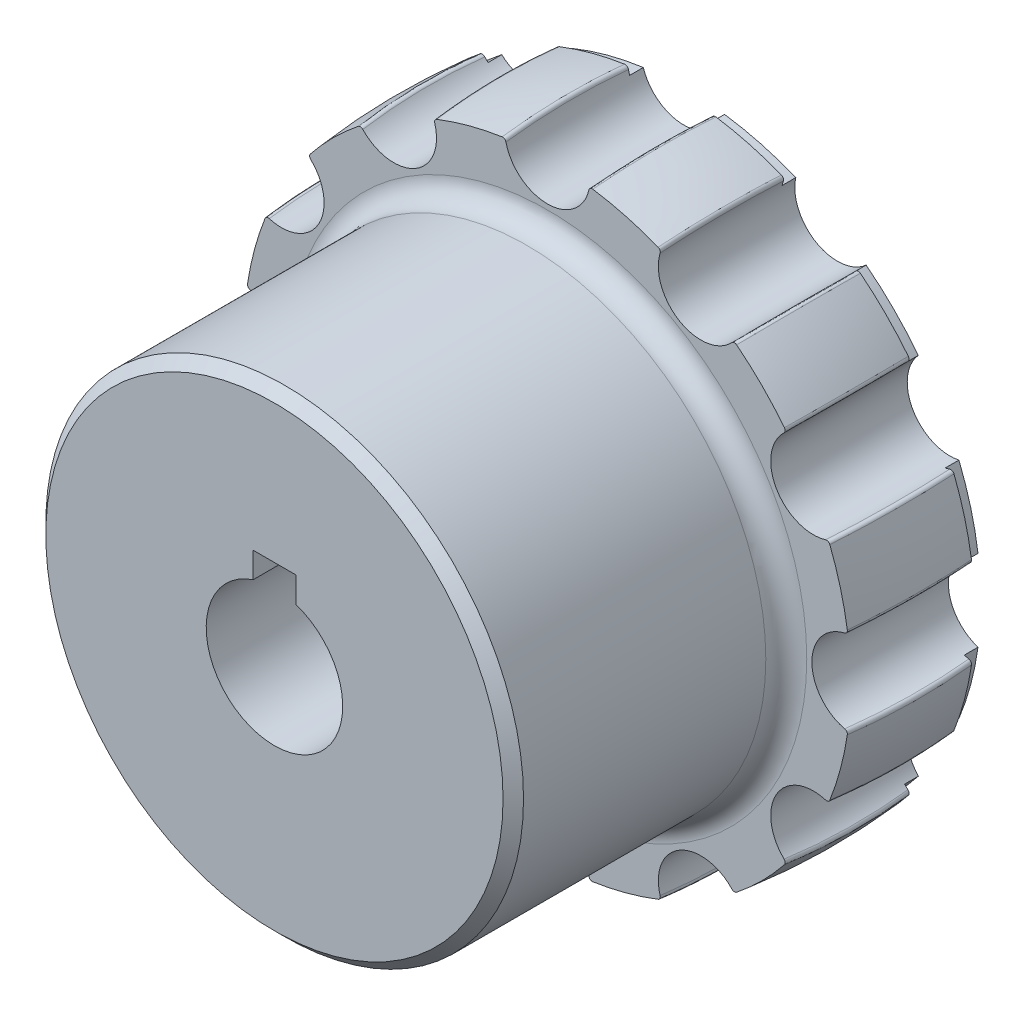
SolidWorks part; units mm, degrees
ref_plane "前视" through (0, 0, 0) normal (0, 0, 1) x (1, 0, 0)
ref_plane "上视" through (0, 0, 0) normal (0, 1, 0) x (1, 0, 0)
ref_plane "右视" through (0, 0, 0) normal (1, 0, 0) x (0, 0, -1)
sketch "草图1" plane through (0, 0, 0) normal (0, 0, 1) x (1, 0, 0)
  circle A0 centre (0, 0) radius 130
  dimension "D1" = 260
extrude "凸台-拉伸1" add sketch "草图1" along normal blind 40
sketch "草图2" plane through (0, 0, 0) normal (0, 0, 1) x (1, 0, 0)
  circle A0 centre (0, 0) radius 70
extrude "凸台-拉伸2" add sketch "草图2" along normal blind 120
sketch "草图3" plane through (0, 0, 0) normal (0, 1, 0) x (1, 0, 0)
  line L0 (0, 59.3731) -> (0, -282.5672) construction
  line L1 (130, -20) -> (-98.4903, -20) construction
  line L2 (130, -40) -> (130, 0) construction
  line L3 (-87, 0) -> (-87, -4)
  line L4 (130, 0) -> (-130, 0) construction
  line L5 (-87, -4) -> (-89.2875, -4)
  line L6 (-88.8854, -40) -> (0, -40) construction
  line L7 (-130, -40) -> (130, -40) construction
  line L8 (0, -40) -> (0, 0) construction
  line L9 (0, 0) -> (-87, 0) construction
  line L10 (-87, 0) -> (-140, 0)
  line L11 (-140, 0) -> (-140, -40)
  line L12 (-140, -40) -> (-88.8854, -40)
  line L13 (-130, 0) -> (-130, -40) construction
  line L14 (-90, -20) -> (-90, 22.025) construction
  arc A0 (-89.2875, -4) -> (-88.8854, -40) centre (90, -20) ccw
  dimension "D1" = 360
  dimension "D3" = 3
  dimension "D2" = 90
  dimension "D4" = 4
  dimension "D5" = 10
revolve "切除-旋转1" cut sketch "草图3" angle 360 about L0
sketch "草图4" plane through (0, 0, 40) normal (0, 0, 1) x (1, 0, 0)
  circle A0 centre (0, 0) radius 90 construction
  circle A1 centre (0, 90) radius 12.5
  circle A2 centre (45, 77.9423) radius 12.5
  circle A3 centre (77.9423, 45) radius 12.5
  circle A4 centre (90, 0) radius 12.5
  circle A5 centre (77.9423, -45) radius 12.5
  circle A6 centre (45, -77.9423) radius 12.5
  circle A7 centre (0, -90) radius 12.5
  circle A8 centre (-45, -77.9423) radius 12.5
  circle A9 centre (-77.9423, -45) radius 12.5
  circle A10 centre (-90, 0) radius 12.5
  circle A11 centre (-77.9423, 45) radius 12.5
  circle A12 centre (-45, 77.9423) radius 12.5
  dimension "D1" = 180
  dimension "D2" = 25
  dimension "D3" = 12
extrude "切除-拉伸1" cut sketch "草图4" against normal blind 70
fillet "圆角1" radius 6 1 edges at (70, 0, 40)
chamfer "倒角1" distance 3 angle 45 1 edges at (70, 0, 120)
fillet "圆角2" radius 1 24 edges at (-88.9043, 12.4519, 29.0559) (-89.0614, -12.4647, 14.9611) (-70.7674, 55.2358, 29.0559) (-83.3618, 33.736, 14.9611) (-33.6685, 83.2193, 29.0559) (-55.3255, 70.8971, 14.9611) (12.4519, 88.9043, 29.0559) (-12.4647, 89.0614, 14.9611) (55.2358, 70.7674, 29.0559) (33.736, 83.3618, 14.9611) (83.2193, 33.6685, 29.0559) (70.8971, 55.3255, 14.9611) (88.9043, -12.4519, 29.0559) (89.0614, 12.4647, 14.9611) (70.7674, -55.2358, 29.0559) (83.3618, -33.736, 14.9611) (33.6685, -83.2193, 29.0559) (55.3255, -70.8971, 14.9611) (-12.4519, -88.9043, 29.0559) (12.4647, -89.0614, 14.9611) (-55.2358, -70.7674, 29.0559) (-33.736, -83.3618, 14.9611) (-83.2193, -33.6685, 29.0559) (-70.8971, -55.3255, 14.9611)
scale "缩放比例1" scale about centroid uniform scaling yes scale factor 0.2
sketch "草图6" plane through (0, 0, 67.7184) normal (0, 0, 1) x (1, 0, 0)
  circle A0 centre (0, 0) radius 4
  dimension "D1" = 8
extrude "切除-拉伸2" cut sketch "草图6" against normal through all
sketch "草图9" plane through (0, 0, 67.7184) normal (0, 0, 1) x (1, 0, 0)
  line L2 (-1.25, 3.7997) -> (-1.25, 5.2997)
  line L3 (1.25, 3.7997) -> (1.25, 5.2997)
  line L4 (-1.25, 5.2997) -> (1.25, 5.2997)
  circle A0 centre (0, 0) radius 4 construction
  arc A1 (1.25, 3.7997) -> (-1.25, 3.7997) centre (0, 0) ccw
  dimension "D1" = 2.5
  dimension "D3" = 1.5
  dimension "D4" = 1.5
extrude "切除-拉伸3" cut sketch "草图9" against normal through all
